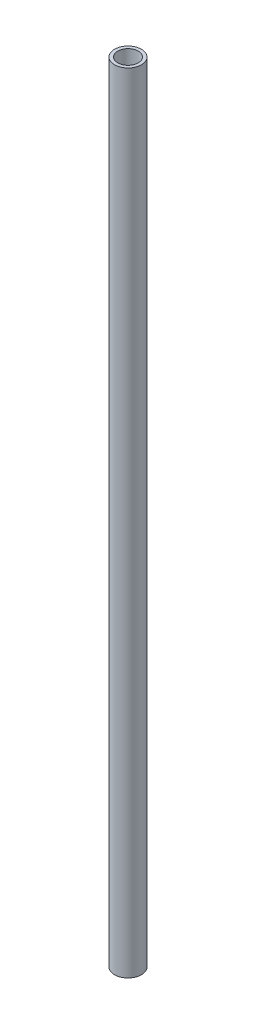
SolidWorks part; units mm, degrees
material "PVC"
ref_plane "Front" through (0, 0, 0) normal (0, 0, 1) x (1, 0, 0)
ref_plane "Top" through (0, 0, 0) normal (0, 1, 0) x (1, 0, 0)
ref_plane "Right" through (0, 0, 0) normal (1, 0, 0) x (0, 0, -1)
sketch "Sketch1" plane through (0, 0, 0) normal (0, 1, 0) x (1, 0, 0)
  circle A0 centre (0, 0) radius 21
  dimension "D1" = 42
extrude "Extrude-Thin1" add sketch "Sketch1" along normal mid plane 1230 thin thin type one direction reverse wall 5
